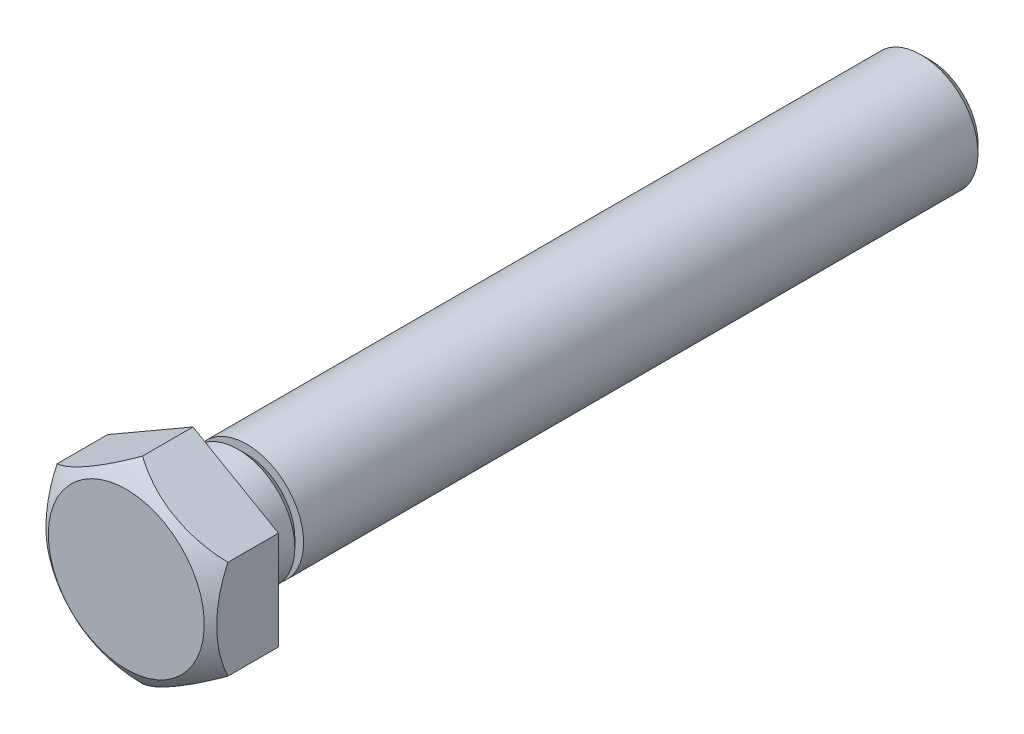
SolidWorks part; units mm, degrees
material "1.0050 (E295)"
ref_plane "Płaszczyzna przednia" through (0, 0, 0) normal (0, 0, 1) x (1, 0, 0)
ref_plane "Płaszczyzna górna" through (0, 0, 0) normal (0, 1, 0) x (1, 0, 0)
ref_plane "Płaszczyzna prawa" through (0, 0, 0) normal (1, 0, 0) x (0, 0, -1)
ref_plane "Płaszczyzna1" through (0, 0, 0.6) normal (0, 0, -1) x (-1, 0, 0)
sketch "Szkic1" plane through (0, 0, 0.6) normal (0, 0, -1) x (-1, 0, 0)
  line L0 (-10.5, -6.0622) -> (0, -12.1243)
  line L1 (0, -12.1243) -> (10.5, -6.0622)
  line L2 (10.5, -6.0622) -> (10.5, 6.0622)
  line L3 (10.5, 6.0622) -> (0, 12.1243)
  line L4 (0, 12.1243) -> (-10.5, 6.0622)
  line L5 (-10.5, 6.0622) -> (-10.5, -6.0622)
  circle A0 centre (0, 0) radius 12.1243
  circle A1 centre (0, 0) radius 12.1243
  circle A2 centre (0, 0) radius 12.1244
  circle A3 centre (0, 0) radius 12.1243
  circle A4 centre (0, 0) radius 12.1243
  circle A5 centre (0, 0) radius 12.1244
extrude "Dodanie-wyciągnięcie1" add sketch "Szkic1" against normal blind 8.2 contours L4 L5 L0 L1 L2 L3
sketch "Szkic2" plane through (0, 0, 0) normal (0, 1, 0) x (1, 0, 0)
  line L0 (7, 90) -> (0, 90)
  line L1 (0, 90) -> (0, -0.6)
  line L2 (0, -0.6) -> (9.685, -0.6)
  line L3 (9.685, -0.6) -> (9.685, 0)
  line L4 (9.685, 0) -> (7, 0)
  line L5 (7, 0) -> (7, 4.9175)
  line L6 (7, 4.9175) -> (5.9175, 6)
  line L7 (5.9175, 6) -> (7, 6)
  line L8 (7, 6) -> (7, 90)
  line L9 (0, 90) -> (0, -0.6) construction
revolve "Obrót1" add sketch "Szkic2" angle 360 about L9
fillet "Zaokrąglenie1" radius 0.1 1 edges at (9.685, 0, 0)
chamfer "Sfazowanie1" distance 1.0825 angle 45 1 edges at (7, 0, -90)
fillet "Zaokrąglenie3" radius 0.6 1 edges at (7, 0, 0)
ref_axis "Oś1" through (0, 0, -88.9175) along (0, 0, 1)
sketch "Szkic3" plane through (0, 0, 0) normal (0, 1, 0) x (1, 0, 0)
  line L1 (-17, 4.7) -> (-17, -11.3)
  line L2 (-17, -11.3) -> (-1, -11.3)
  line L3 (0, -8.8) -> (10.5, -8.8) construction
  arc A0 (-17, 4.7) -> (-1, -11.3) centre (-1, 4.7) ccw
  dimension "D1" = 32
  dimension "D2" = 1
  dimension "D3" = 2.5
revolve "Wycięcie-obrót1" cut sketch "Szkic3" angle 360 about axis through (0, 0, -88.9175) along (0, 0, 1)
